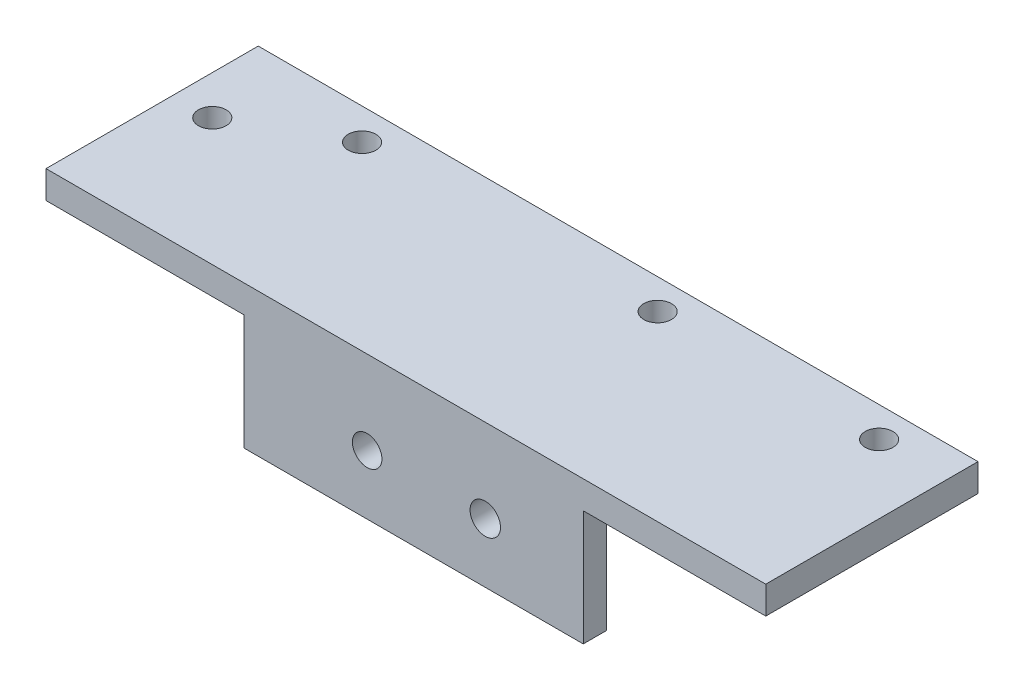
SolidWorks part; units mm, degrees
ref_plane "前视基准面" through (0, 0, 0) normal (0, 0, 1) x (1, 0, 0)
ref_plane "上视基准面" through (0, 0, 0) normal (0, 1, 0) x (1, 0, 0)
ref_plane "右视基准面" through (0, 0, 0) normal (1, 0, 0) x (0, 0, -1)
other "Configuration Table"
sketch "草图1" plane through (0, 0, 0) normal (0, 1, 0) x (1, 0, 0)
  line L1 (-39, -7.5) -> (39, -7.5)
  line L2 (-39, -7.5) -> (-39, 7.5)
  line L3 (-39, 7.5) -> (39, 7.5)
  line L4 (39, -7.5) -> (39, 7.5)
  line L5 (-39, -7.5) -> (39, 7.5) construction
  line L6 (-39, 7.5) -> (39, -7.5) construction
  point P0 (0, 0)
  dimension "D1" = 15
  dimension "D2" = 78
extrude "凸台-拉伸1" add sketch "草图1" along normal blind 3 contours L2 L1 L4 L3
sketch "草图3" plane through (0, 3, 0) normal (0, 1, 0) x (1, 0, 0)
  line L0 (-39, -7.5) -> (-39, 7.5) construction
  line L1 (-39, 7.5) -> (39, 7.5) construction
  circle A0 centre (-34.76, -1.72) radius 1.5
  circle A1 centre (-24.35, 4.1) radius 1.5
  circle A2 centre (31.56, 4.2217) radius 1.5
  circle A3 centre (7.56, 4.2217) radius 1.5
  point P2 (0, 0)
  point P11 (27.5737, 4.2217)
  point P12 (6.7297, 4.2217)
  point P13 (-31.0334, 4.2217)
  point P14 (-26.0415, 4.2217)
  point P17 (-24.5173, 0.3349)
  dimension "D1" = 4.24
  dimension "D2" = 10.41
  dimension "D3" = 3.4
  dimension "D4" = 5.82
  dimension "D5" = 31.91
  dimension "D6" = 24
extrude "切除-拉伸1" cut sketch "草图3" against normal blind 3
sketch "草图4" plane through (0, 3, 0) normal (0, 1, 0) x (1, 0, 0)
  line L0 (-39, -7.5) -> (-39, 7.5) construction
  circle A0 centre (-3, -1.2342) radius 6
  point P4 (-3, -1.2342)
  dimension "D1" = 36
extrude "凸台-拉伸2" add sketch "草图4" along normal blind 18
sketch "草图5" plane through (0, 21, 0) normal (0, 1, 0) x (1, 0, 0)
  circle A0 centre (-3, -1.2342) radius 4.5
extrude "切除-拉伸2" cut sketch "草图5" against normal blind 21
hole_wizard "Ø2.0mm 暗销孔2" positions "3D草图5" profile "草图8" hole size "Ø2.0" standard "ANSI Metric"
sketch3d "3D草图5"
  point P0 (-7.9013, 17.3421, 4.6949)
  point P2 (1.0718, 17.1648, 5.6411)
sketch "草图8" plane through (-7.9013, 17.3421, 4.6949) normal (0, 1, 0) x (0.5768, 0, 0.8169)
  line L0 (0, 0) -> (0, 6)
  line L1 (0, 6) -> (1.5, 4.5)
  line L2 (1.5, 4.5) -> (1.5, 0)
  line L5 (1.5, 0) -> (0, 0)
  line L10 (0, 6) -> (-1.5, 4.5) construction
  line L11 (0, -6.35) -> (0, 107.95) construction
  dimension "孔直径" = 3
  dimension "孔深度" = 6
  dimension "导头角度" = 90
sketch "草图10" plane through (0, 0, -7.5) normal (0, 0, -1) x (-1, 0, 0)
  line L0 (39, 3) -> (-39, 3) construction
  line L1 (0, 3) -> (6, 3)
  line L2 (0, 3) -> (0, 13)
  line L3 (0, 13) -> (6, 13)
  line L4 (6, 3) -> (6, 13)
  point P6 (6.8148, 13.7899)
  point P7 (6.7809, 13.0053)
  point P8 (0, 0)
  point P9 (7.0332, 12.5658)
  dimension "D1" = 6
  dimension "D2" = 10
extrude "切除-拉伸3" cut sketch "草图10" against normal blind 7
sketch "草图13" plane through (0, 0, -7.5) normal (0, 0, -1) x (-1, 0, 0)
  line L0 (39, 3) -> (-39, 3) construction
  line L1 (-6.6034, 3) -> (13.2323, 3)
  line L2 (-6.6034, 3) -> (-6.6034, 24.6102)
  line L3 (-6.6034, 24.6102) -> (13.2323, 24.6102)
  line L4 (13.2323, 3) -> (13.2323, 24.6102)
extrude "切除-拉伸4" cut sketch "草图13" against normal blind 20
sketch "草图14" plane through (0, 3, 0) normal (0, 1, 0) x (1, 0, 0)
  line L1 (-8.751, 3.9817) -> (2.7721, 3.9817)
  line L2 (-8.751, 3.9817) -> (-8.751, -6.5086)
  line L3 (-8.751, -6.5086) -> (2.7721, -6.5086)
  line L4 (2.7721, 3.9817) -> (2.7721, -6.5086)
extrude "凸台-拉伸3" add sketch "草图14" against normal blind 3
sketch "草图18" plane through (0, 0, 0) normal (0, -1, 0) x (1, 0, 0)
  line L1 (-39, 7.5) -> (39, 7.5)
  line L2 (-39, 7.5) -> (-39, 15.5)
  line L3 (-39, 15.5) -> (39, 15.5)
  line L4 (39, 7.5) -> (39, 15.5)
  dimension "D1" = 8
extrude "凸台-拉伸4" add sketch "草图18" against normal blind 3
sketch "草图19" plane through (0, 0, 0) normal (0, -1, 0) x (1, 0, 0)
  line L0 (39, 15.5) -> (-39, 15.5) construction
  line L1 (-17.5447, 15.5) -> (19.2232, 15.5)
  line L2 (-17.5447, 15.5) -> (-17.5447, 13)
  line L3 (-17.5447, 13) -> (19.2232, 13)
  line L4 (19.2232, 15.5) -> (19.2232, 13)
  dimension "D1" = 2.5
extrude "凸台-拉伸5" add sketch "草图19" along normal blind 12.5
sketch "草图20" plane through (0, 0, 13) normal (0, 0, -1) x (-1, 0, 0)
  circle A0 centre (-6.7687, -6.2144) radius 1.65
  circle A1 centre (6.2313, -6.2144) radius 1.65
  point P4 (0, 0)
  point P5 (0, 0)
  point P6 (1.0873, -6.2144)
  dimension "D1" = 13
sketch "草图23" plane through (0, 0, 13) normal (0, 0, -1) x (-1, 0, 0)
  line L0 (-19.2232, -12.5) -> (-19.2232, 0) construction
  circle A4 centre (-8.6032, -6.0559) radius 1.65
  circle A5 centre (2.5968, -6.0559) radius 1.65
  dimension "D1" = 10.62
  dimension "D2" = 11.2
extrude "切除-拉伸6" cut sketch "草图23" against normal blind 12.5
sketch "草图24" plane through (0, 0, 13) normal (0, 0, -1) x (-1, 0, 0)
  circle A0 centre (-8.6032, -6.0559) radius 1.65 construction
  circle A1 centre (-8.6032, -6.0559) radius 1.65
  circle A2 centre (2.5968, -6.0559) radius 1.65 construction
  circle A3 centre (2.5968, -6.0559) radius 1.65
  circle A4 centre (4.1968, -6.0559) radius 1.6
  dimension "D2" = 12.8
  dimension "D1" = 11.2
sketch "草图25" plane through (0, 0, 13) normal (0, 0, -1) x (-1, 0, 0)
  line L1 (0.2124, -3.7444) -> (4.449, -3.7444)
  line L2 (0.2124, -3.7444) -> (0.2124, -9.1085)
  line L3 (0.2124, -9.1085) -> (4.449, -9.1085)
  line L4 (4.449, -3.7444) -> (4.449, -9.1085)
extrude "凸台-拉伸7" add sketch "草图25" against normal blind 2.5
sketch "草图26" plane through (0, 0, 13) normal (0, 0, -1) x (-1, 0, 0)
  circle A0 centre (4.1968, -6.0559) radius 1.6 construction
  circle A1 centre (4.1968, -6.0559) radius 1.6
extrude "切除-拉伸7" cut sketch "草图26" against normal blind 2.5
